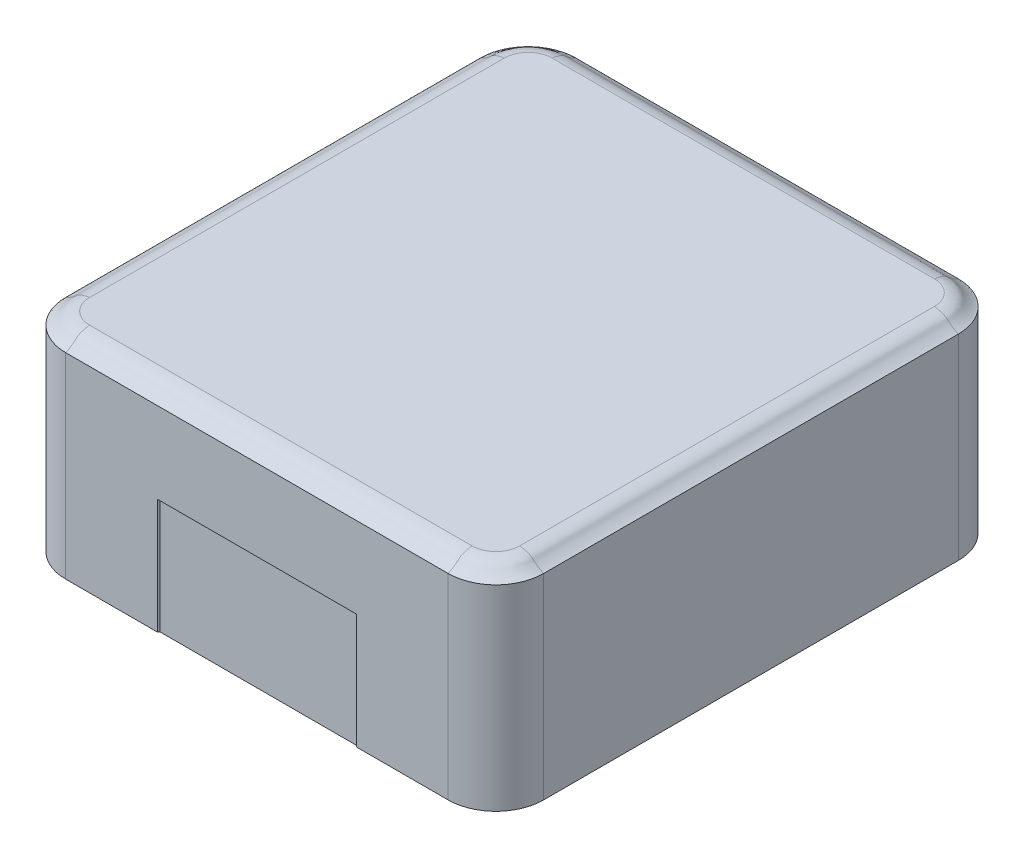
SolidWorks part; units mm, degrees
ref_plane "前视基准面" through (0, 0, 0) normal (0, 0, 1) x (1, 0, 0)
ref_plane "上视基准面" through (0, 0, 0) normal (0, 1, 0) x (1, 0, 0)
ref_plane "右视基准面" through (0, 0, 0) normal (1, 0, 0) x (0, 0, -1)
sketch "草图1" plane through (0, 0, 0) normal (0, 1, 0) x (1, 0, 0)
  line L1 (-6.3, 6.725) -> (6.3, 6.725)
  line L2 (-6.3, 6.725) -> (-6.3, -6.725)
  line L3 (-6.3, -6.725) -> (6.3, -6.725)
  line L4 (6.3, 6.725) -> (6.3, -6.725)
  line L5 (-6.3, 6.725) -> (6.3, -6.725) construction
  line L6 (-6.3, -6.725) -> (6.3, 6.725) construction
  point P0 (0, 0)
  dimension "D1" = 12.6
  dimension "D2" = 13.45
extrude "凸台-拉伸1" add sketch "草图1" along normal blind 5.8
fillet "圆角1" radius 1.26 4 edges at (6.3, 2.9, -6.725) (-6.3, 2.9, -6.725) (-6.3, 2.9, 6.725) (6.3, 2.9, 6.725)
sketch "草图2" plane through (0, 0, 0) normal (0, -1, 0) x (1, 0, 0)
  line L0 (0, 6.725) -> (0, -6.725) construction
  line L1 (-5.04, 6.725) -> (5.04, 6.725) construction
  line L2 (5.04, -6.725) -> (-5.04, -6.725) construction
  line L3 (6.3, 0) -> (-6.3, 0) construction
  line L4 (2.75, 4.225) -> (-2.75, 4.225)
  line L5 (2.75, 4.225) -> (2.75, 6.725)
  line L6 (2.75, 6.725) -> (-2.75, 6.725)
  line L7 (-2.75, 4.225) -> (-2.75, 6.725)
  line L8 (2.75, 4.225) -> (-2.75, 6.725) construction
  line L9 (2.75, 6.725) -> (-2.75, 4.225) construction
  line L10 (6.3, 5.465) -> (6.3, -5.465) construction
  line L11 (-6.3, -5.465) -> (-6.3, 5.465) construction
  line L12 (2.75, -6.725) -> (-2.75, -4.225) construction
  line L13 (2.75, -4.225) -> (-2.75, -6.725) construction
  line L14 (-2.75, -4.225) -> (-2.75, -6.725)
  line L15 (2.75, -6.725) -> (-2.75, -6.725)
  line L16 (2.75, -4.225) -> (2.75, -6.725)
  line L17 (2.75, -4.225) -> (-2.75, -4.225)
  point P6 (0, 5.475)
  point P21 (0, -5.475)
  dimension "D1" = 5.5
  dimension "D2" = 2.5
extrude "切除-拉伸1" cut sketch "草图2" against normal blind 0.15
ref_plane "基准面1" through (-5.04, 0, 0) normal (1, 0, 0) x (0, 0, -1)
sketch "草图3" plane through (-5.04, 0, 0) normal (1, 0, 0) x (0, 0, -1)
  line L0 (-6.725, 5.8) -> (-6.725, 0) construction
  line L1 (-5.465, 5.8) -> (-6.725, 5.8) construction
  line L2 (-6.095, 5.8) -> (-6.725, 5.8)
  line L3 (-6.725, 5.8) -> (-6.725, 5.485)
  line L4 (5.465, 5.8) -> (-5.465, 5.8) construction
  line L5 (-6.41, 5.8) -> (-6.41, 5.6992) construction
  line L6 (-6.725, 5.6425) -> (-6.473, 5.6425) construction
  spline S0 degree 3 poles (-6.095, 5.8) (-6.1153, 5.8) (-6.3692, 5.7571) (-6.5082, 5.5955) (-6.7092, 5.485) (-6.725, 5.485) knots 0 0 0 0 0.464083 0.583014 1 1 1 1
  point P3 (0, 0)
  point P11 (-1.2141, 0.975)
  point P14 (-1.2, 0.9833)
  point P15 (-1.2108, 0.975)
  point P18 (-1.2108, 0.975)
  point P19 (-1.2114, 0.975)
  point P20 (-1.2, 0.9833)
  dimension "D1" = 0.63
  dimension "D2" = 0.315
  dimension "D3" = 0.1008
  dimension "D4" = 0.252
curve "组合曲线1"
sweep "切除-扫描1" cut profiles "草图3" path "组合曲线1"
ref_plane "基准面2" through (0, 2.9, 0) normal (0, 1, 0) x (1, 0, 0)
mirror "镜向1" about plane through (0, 2.9, 0) normal (0, 1, 0) of "切除-扫描1"
sketch "草图4" plane through (0, 0.15, 0) normal (0, 1, 0) x (1, 0, 0)
  line L0 (0, -6.725) -> (0, -6.65) construction
  line L2 (5.04, -6.725) -> (-5.04, -6.725) construction
  line L8 (2.625, -6.65) -> (-2.625, -6.65)
  line L9 (2.625, -6.65) -> (2.625, -6.725)
  line L10 (2.625, -6.725) -> (-2.625, -6.725)
  line L11 (-2.625, -6.65) -> (-2.625, -6.725)
  line L12 (2.625, -6.65) -> (-2.625, -6.725) construction
  line L13 (2.625, -6.725) -> (-2.625, -6.65) construction
  point P5 (0, -6.6875)
  dimension "D1" = 5.25
  dimension "D2" = 0.075
extrude "切除-拉伸2" cut sketch "草图4" along normal blind 3.2
mirror "镜向2" about plane through (0, 0, 0) normal (0, 0, 1) of "切除-拉伸2"
equation "\"D1@草图1\"=\"A\""
equation "\"D2@草图1\"=\"B\""
equation "\"D1@凸台-拉伸1\"=\"C\""
equation "\"D1@圆角1\"=0.1*\"A\""
equation "\"D1@草图2\"=1.1*\"E\""
equation "\"D2@草图2\"=0.1*\"E\"+\"D\""
equation "\"D1@草图3\"=0.05*\"A\""
equation "\"D2@草图3\"=0.025*\"A\""
equation "\"A\"= 12.6mm'宽度"
equation "\"B\"= 13.45mm'长度"
equation "\"C\"= 5.8mm'高度"
equation "\"D\"= 2.0mm'引脚宽度"
equation "\"E\"= 5.0mm'引脚长度"
equation "\"F\"= 0.3mm'引脚厚度"
equation "\"D1@切除-拉伸1\"=0.5*\"F\""
equation "\"D1@切除-拉伸2\"=0.5*\"C\"+\"F\""
equation "\"D3@草图3\"=0.008*\"A\""
equation "\"D4@草图3\"=0.02*\"A\""
equation "\"D1@草图4\"=1.05*\"E\""
equation "\"D2@草图4\"=0.25*\"F\""
